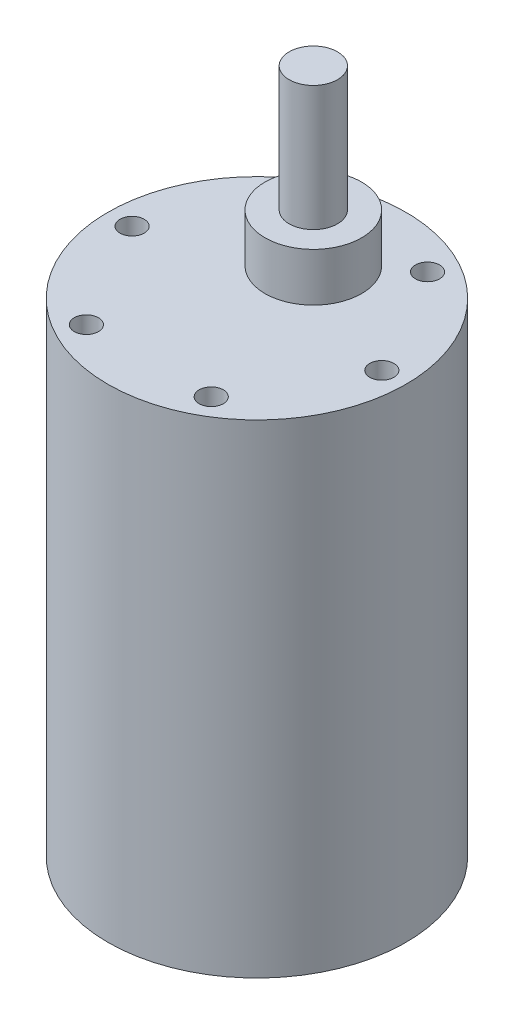
SolidWorks part; units mm, degrees
material "1060 合金"
ref_plane "前视基准面" through (0, 0, 0) normal (0, 0, 1) x (1, 0, 0)
ref_plane "上视基准面" through (0, 0, 0) normal (0, 1, 0) x (1, 0, 0)
ref_plane "右视基准面" through (0, 0, 0) normal (1, 0, 0) x (0, 0, -1)
sketch "草图1" plane through (0, 0, 0) normal (0, 1, 0) x (1, 0, 0)
  circle A0 centre (0, 0) radius 18.5
  dimension "D1" = 37
extrude "凸台-拉伸1" add sketch "草图1" along normal blind 60
sketch "草图2" plane through (0, 60, 0) normal (0, 1, 0) x (1, 0, 0)
  circle A0 centre (0, 7) radius 6
  dimension "D1" = 7
  dimension "D2" = 12
extrude "凸台-拉伸2" add sketch "草图2" along normal blind 6
sketch "草图4" plane through (0, 66, 0) normal (0, 1, 0) x (1, 0, 0)
  circle A0 centre (0, 7) radius 3
  dimension "D1" = 6
extrude "凸台-拉伸3" add sketch "草图4" along normal blind 15.5
sketch "草图3" plane through (0, 60, 0) normal (0, 1, 0) x (1, 0, 0)
  circle A2 centre (-7.75, 13.4234) radius 1.5
  dimension "D1" = 3
extrude "切除-拉伸1" cut sketch "草图3" against normal blind 5
pattern_circular "阵列(圆周)2" count 6 over 360 about axis through (0, 0, 0) along (0, 1, 0) of "切除-拉伸1"
